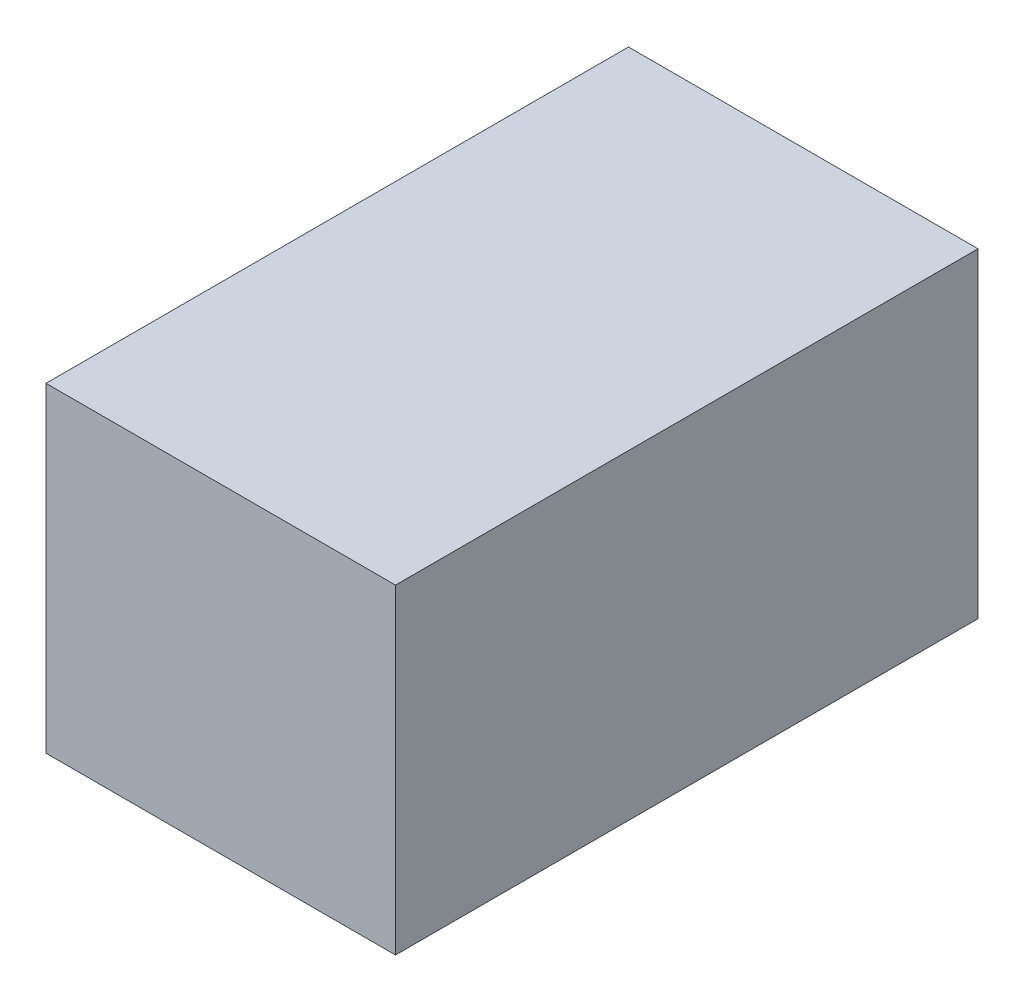
SolidWorks part; units mm, degrees
ref_plane "正面" through (0, 0, 0) normal (0, 0, 1) x (1, 0, 0)
ref_plane "平面" through (0, 0, 0) normal (0, 1, 0) x (1, 0, 0)
ref_plane "右側面" through (0, 0, 0) normal (1, 0, 0) x (0, 0, -1)
sketch "ｽｹｯﾁ1" plane through (0, 0, 0) normal (0, 0, 1) x (1, 0, 0)
  line L1 (6, 5.5) -> (-6, 5.5)
  line L2 (6, 5.5) -> (6, -5.5)
  line L3 (6, -5.5) -> (-6, -5.5)
  line L4 (-6, 5.5) -> (-6, -5.5)
  line L5 (6, 5.5) -> (-6, -5.5) construction
  line L6 (6, -5.5) -> (-6, 5.5) construction
  point P0 (0, 0)
  dimension "D1" = 11
  dimension "D2" = 12
extrude "ﾎﾞｽ - 押し出し1" add sketch "ｽｹｯﾁ1" along normal blind 20
sketch "ｽｹｯﾁ2" plane through (0, 0, 0) normal (0, 0, -1) x (-1, 0, 0)
  circle A0 centre (0, 0) radius 1.5
  dimension "D1" = 3
extrude "ﾎﾞｽ - 押し出し2" add sketch "ｽｹｯﾁ2" along normal blind 1
sketch "ｽｹｯﾁ3" plane through (0, 0, 0) normal (0, 0, -1) x (-1, 0, 0)
  circle A0 centre (0, 0) radius 0.75
  dimension "D1" = 1.5
extrude "ﾎﾞｽ - 押し出し3" add sketch "ｽｹｯﾁ3" along normal blind 4.5
